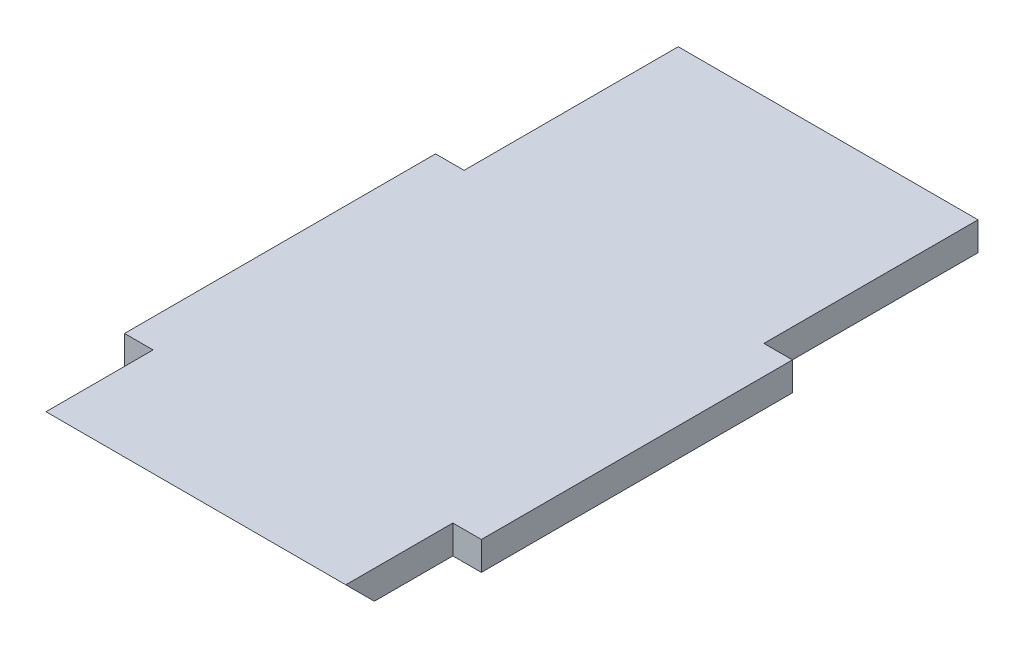
SolidWorks part; units mm, degrees
ref_plane "Front Plane" through (0, 0, 0) normal (0, 0, 1) x (1, 0, 0)
ref_plane "Top Plane" through (0, 0, 0) normal (0, 1, 0) x (1, 0, 0)
ref_plane "Right Plane" through (0, 0, 0) normal (1, 0, 0) x (0, 0, -1)
sketch "Sketch1" plane through (0, 0, 0) normal (0, 1, 0) x (1, 0, 0)
  line L0 (0, 117.16) -> (8, 117.16)
  line L1 (0, 0) -> (100, 0)
  line L2 (0, 0) -> (0, 177.16)
  line L3 (0, 177.16) -> (100, 177.16)
  line L4 (100, 0) -> (100, 177.16)
  line L5 (8, 117.16) -> (8, 177.16)
  line L6 (0, 30) -> (8, 30)
  line L7 (8, 30) -> (8, 0)
  line L8 (50, 0) -> (50, 66.2245) construction
  line L9 (100, 30) -> (92, 30)
  line L10 (92, 30) -> (92, 0)
  line L11 (100, 117.16) -> (92, 117.16)
  line L12 (92, 117.16) -> (92, 177.16)
  dimension "D1" = 100
  dimension "D2" = 177.16
  dimension "D3" = 8
  dimension "D4" = 8
  dimension "D5" = 60
  dimension "D6" = 30
extrude "Boss-Extrude1" add sketch "Sketch1" along normal blind 8
sketch "Sketch2" plane through (8, 0, 0) normal (-1, 0, 0) x (0, 0, 1)
  line L0 (0, 8) -> (-8, 0)
  line L1 (-30, 0) -> (0, 0) construction
  line L2 (-8, 0) -> (0, 0)
  line L3 (0, 0) -> (0, 8)
extrude "Cut-Extrude1" cut sketch "Sketch2" against normal through all
